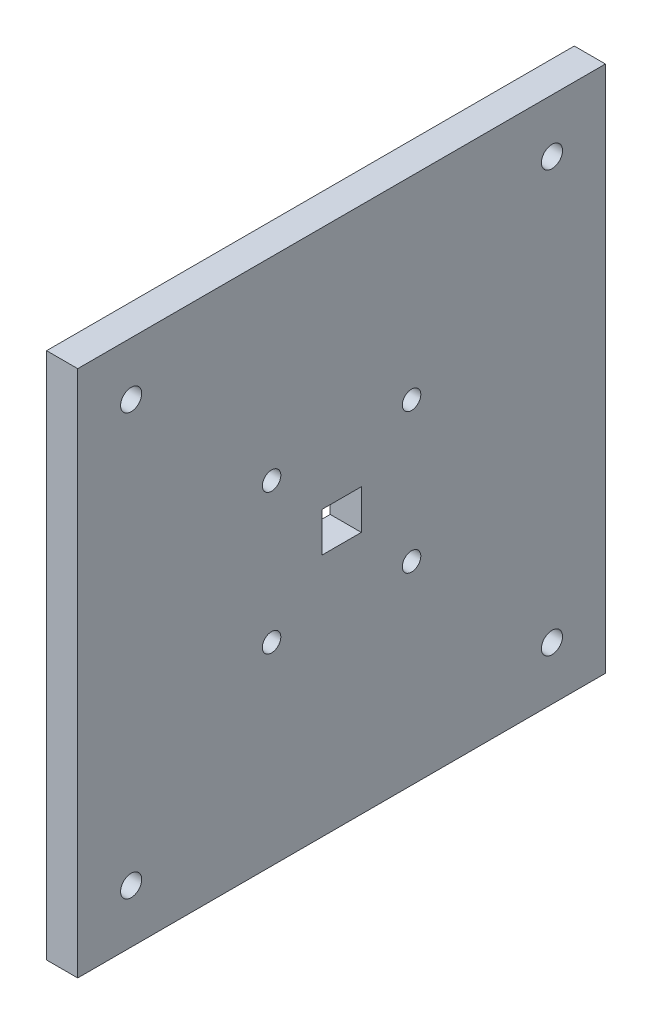
SolidWorks part; units mm, degrees
ref_plane "Front Plane" through (0, 0, 0) normal (0, 0, 1) x (1, 0, 0)
ref_plane "Top Plane" through (0, 0, 0) normal (0, 1, 0) x (1, 0, 0)
ref_plane "Right Plane" through (0, 0, 0) normal (1, 0, 0) x (0, 0, -1)
sketch "Sketch1" plane through (0, 0, 0) normal (1, 0, 0) x (0, 0, -1)
  line L1 (-50.8, -50.8) -> (50.8, -50.8)
  line L2 (-50.8, -50.8) -> (-50.8, 50.8)
  line L3 (-50.8, 50.8) -> (50.8, 50.8)
  line L4 (50.8, -50.8) -> (50.8, 50.8)
  line L5 (-50.8, -50.8) -> (50.8, 50.8) construction
  line L6 (-50.8, 50.8) -> (50.8, -50.8) construction
  line L7 (-40.513, -40.513) -> (40.513, -40.513) construction
  line L8 (-40.513, -40.513) -> (-40.513, 40.513) construction
  line L9 (-40.513, 40.513) -> (40.513, 40.513) construction
  line L10 (40.513, -40.513) -> (40.513, 40.513) construction
  line L11 (-40.513, -40.513) -> (40.513, 40.513) construction
  line L12 (-40.513, 40.513) -> (40.513, -40.513) construction
  line L13 (-13.4747, -13.4747) -> (13.4747, -13.4747) construction
  line L14 (-13.4747, -13.4747) -> (-13.4747, 13.4747) construction
  line L15 (-13.4747, 13.4747) -> (13.4747, 13.4747) construction
  line L16 (13.4747, -13.4747) -> (13.4747, 13.4747) construction
  line L17 (-27.6712, -27.6712) -> (27.6712, 27.6712) construction
  line L18 (-27.6712, 27.6712) -> (27.6712, -27.6712) construction
  line L19 (-13.4747, -13.4747) -> (13.4747, 13.4747) construction
  line L20 (-13.4747, 13.4747) -> (13.4747, -13.4747) construction
  line L21 (3.8057, -3.8057) -> (-3.8143, -3.8057)
  line L22 (3.8057, -3.8057) -> (3.8057, 3.8143)
  line L23 (3.8057, 3.8143) -> (-3.8143, 3.8143)
  line L24 (-3.8143, -3.8057) -> (-3.8143, 3.8143)
  line L25 (-8.0978, -8.0978) -> (8.0978, 8.0978) construction
  line L26 (-8.0978, 8.0978) -> (8.0978, -8.0978) construction
  line L27 (-10.4408, -10.4408) -> (10.4408, 10.4408) construction
  line L28 (-10.4408, 10.4408) -> (10.4408, -10.4408) construction
  line L29 (3.8057, -3.8057) -> (-3.8143, 3.8143) construction
  line L30 (3.8057, 3.8143) -> (-3.8143, -3.8057) construction
  circle A0 centre (-40.513, 40.513) radius 2.032
  circle A1 centre (40.513, 40.513) radius 2.032
  circle A2 centre (40.513, -40.513) radius 2.032
  circle A3 centre (-40.513, -40.513) radius 2.032
  circle A4 centre (-13.4747, 13.4747) radius 1.778
  circle A5 centre (-13.4747, -13.4747) radius 1.778
  circle A6 centre (13.4747, -13.4747) radius 1.778
  circle A7 centre (13.4747, 13.4747) radius 1.778
  point P0 (0, 0)
  point P6 (0, 0)
  point P8 (0, 0)
  point P20 (0, 0)
  point P21 (0, 0)
  point P34 (0, 0)
  point P39 (-0.0043, 0.0043)
extrude "Boss-Extrude1" add sketch "Sketch1" along normal blind 5.9944
